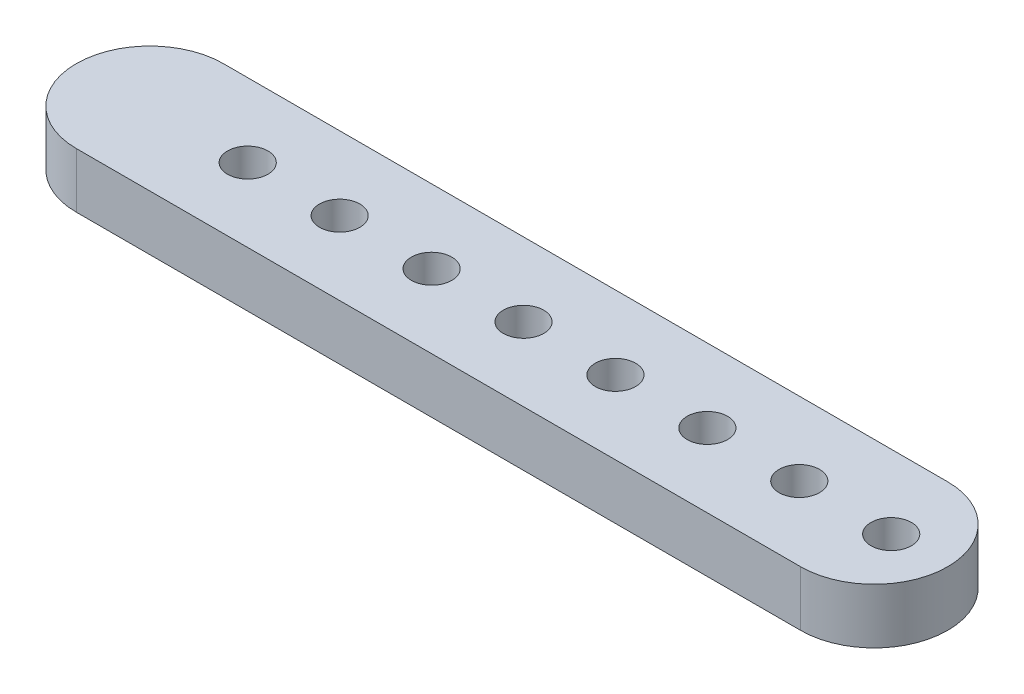
SolidWorks part; units mm, degrees
ref_plane "Front Plane" through (0, 0, 0) normal (0, 0, 1) x (1, 0, 0)
ref_plane "Top Plane" through (0, 0, 0) normal (0, 1, 0) x (1, 0, 0)
ref_plane "Right Plane" through (0, 0, 0) normal (1, 0, 0) x (0, 0, -1)
sketch "Sketch1" plane through (0, 0, 0) normal (0, 1, 0) x (1, 0, 0)
  line L0 (58.8789, 0) -> (78.5789, 0) construction
  line L1 (58.8789, 2) -> (78.5789, 2)
  line L2 (58.8789, -2) -> (78.5789, -2)
  arc A0 (58.8789, 2) -> (58.8789, -2) centre (58.8789, 0) ccw
  arc A1 (78.5789, -2) -> (78.5789, 2) centre (78.5789, 0) ccw
  point P3 (68.7289, 0)
  dimension "D1" = 4
  dimension "D2" = 19.7
extrude "Boss-Extrude1" add sketch "Sketch1" along normal blind 1.5
sketch "Sketch2" plane through (0, 1.5, 0) normal (0, 1, 0) x (1, 0, 0)
  circle A0 centre (79.042, 0) radius 0.55
  circle A1 centre (76.542, 0) radius 0.55
  circle A2 centre (74.042, 0) radius 0.55
  circle A3 centre (71.542, 0) radius 0.55
  circle A4 centre (69.042, 0) radius 0.55
  circle A5 centre (66.542, 0) radius 0.55
  circle A6 centre (64.042, 0) radius 0.55
  circle A7 centre (61.542, 0) radius 0.55
  dimension "D1" = 1.1
  dimension "D2" = 8
extrude "Cut-Extrude1" cut sketch "Sketch2" against normal blind 1.5
scale "Scale1" scale about centroid uniform scaling yes scale factor 2.5
